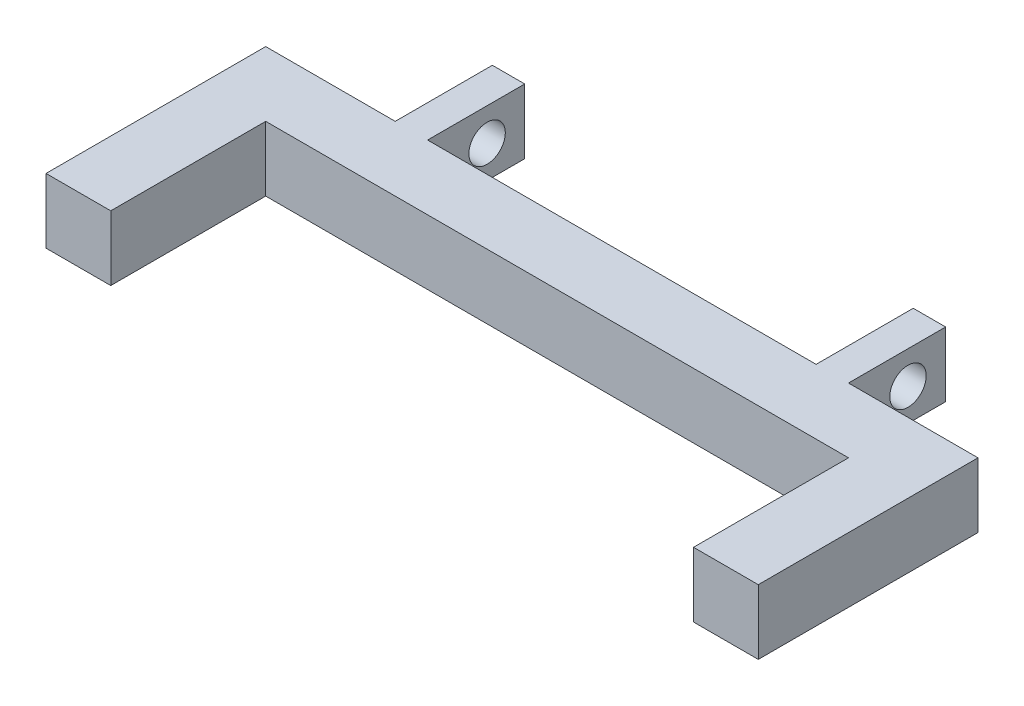
SolidWorks part; units mm, degrees
ref_plane "Front Plane" through (0, 0, 0) normal (0, 0, 1) x (1, 0, 0)
ref_plane "Top Plane" through (0, 0, 0) normal (0, 1, 0) x (1, 0, 0)
ref_plane "Right Plane" through (0, 0, 0) normal (1, 0, 0) x (0, 0, -1)
sketch "Sketch1" plane through (0, 0, 0) normal (0, 1, 0) x (1, 0, 0)
  line L1 (-279.4, -86.1847) -> (279.4, -86.1847)
  line L2 (-279.4, -86.1847) -> (-279.4, 86.1847)
  line L3 (-279.4, 86.1847) -> (279.4, 86.1847)
  line L4 (279.4, -86.1847) -> (279.4, 86.1847)
  line L5 (-279.4, -86.1847) -> (279.4, 86.1847) construction
  line L6 (-279.4, 86.1847) -> (279.4, -86.1847) construction
  line L7 (-228.6, -86.1847) -> (228.6, -86.1847)
  line L8 (-228.6, -86.1847) -> (-228.6, 35.3847)
  line L9 (-228.6, 35.3847) -> (228.6, 35.3847)
  line L10 (228.6, -86.1847) -> (228.6, 35.3847)
  line L11 (-177.8, 86.1847) -> (-152.4, 86.1847)
  line L12 (-177.8, 86.1847) -> (-177.8, 162.3847)
  line L13 (-177.8, 162.3847) -> (-152.4, 162.3847)
  line L14 (-152.4, 86.1847) -> (-152.4, 162.3847)
  line L15 (152.4, 86.1847) -> (177.8, 86.1847)
  line L16 (152.4, 86.1847) -> (152.4, 162.3847)
  line L17 (152.4, 162.3847) -> (177.8, 162.3847)
  line L18 (177.8, 86.1847) -> (177.8, 162.3847)
  point P0 (0, 0)
  point P10 (-279.4, 0)
  dimension "D1" = 50.8
  dimension "D2" = 50.8
  dimension "D3" = 50.8
  dimension "D4" = 457.2
  dimension "D5" = 25.4
  dimension "D6" = 25.4
  dimension "D7" = 152.4
  dimension "D8" = 304.8
  dimension "D9" = 76.2
extrude "Boss-Extrude1" add sketch "Sketch1" along normal blind 50.8 contours L10 L1 L4 L3 L2 L8 L9 | L3 L14 L13 L12 | L3 L18 L17 L16
sketch "Sketch2" plane through (177.8, 0, 0) normal (1, 0, 0) x (0, 0, -1)
  circle A0 centre (132.8595, 25.2733) radius 14.2875
extrude "Cut-Extrude1" cut sketch "Sketch2" against normal through all
